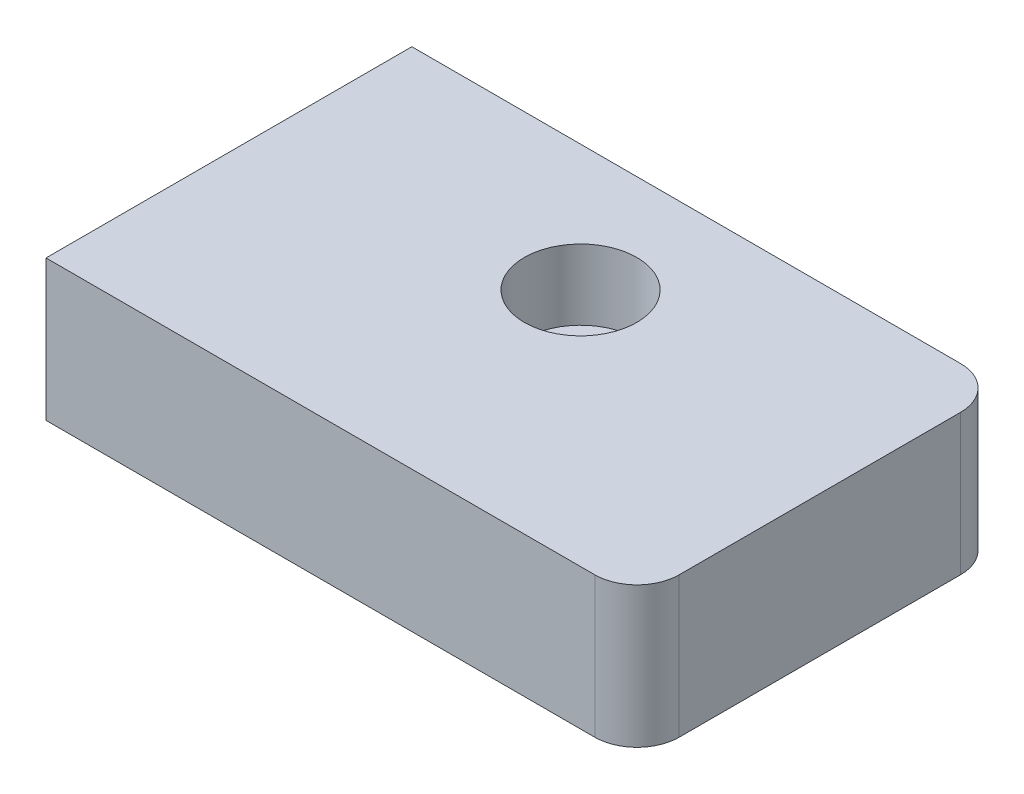
SolidWorks part; units mm, degrees
ref_plane "前视基准面" through (0, 0, 0) normal (0, 0, 1) x (1, 0, 0)
ref_plane "上视基准面" through (0, 0, 0) normal (0, 1, 0) x (1, 0, 0)
ref_plane "右视基准面" through (0, 0, 0) normal (1, 0, 0) x (0, 0, -1)
sketch "草图1" plane through (0, 0, 0) normal (0, 1, 0) x (1, 0, 0)
  line L1 (-21, 13) -> (21, 13)
  line L2 (-21, 13) -> (-21, -13)
  line L3 (-21, -13) -> (21, -13)
  line L4 (21, 13) -> (21, -13)
  line L5 (-21, 13) -> (21, -13) construction
  line L6 (-21, -13) -> (21, 13) construction
  point P0 (0, 0)
  dimension "D1" = 42
  dimension "D2" = 26
extrude "凸台-拉伸1" add sketch "草图1" along normal blind 10
sketch "草图2" plane through (0, 10, 0) normal (0, 1, 0) x (1, 0, 0)
  circle A0 centre (-0.0356, 4.0262) radius 4
  dimension "D1" = 8
extrude "切除-拉伸1" cut sketch "草图2" against normal blind 5
fillet "圆角1" radius 3 2 edges at (21, 5, -13) (21, 5, 13)
